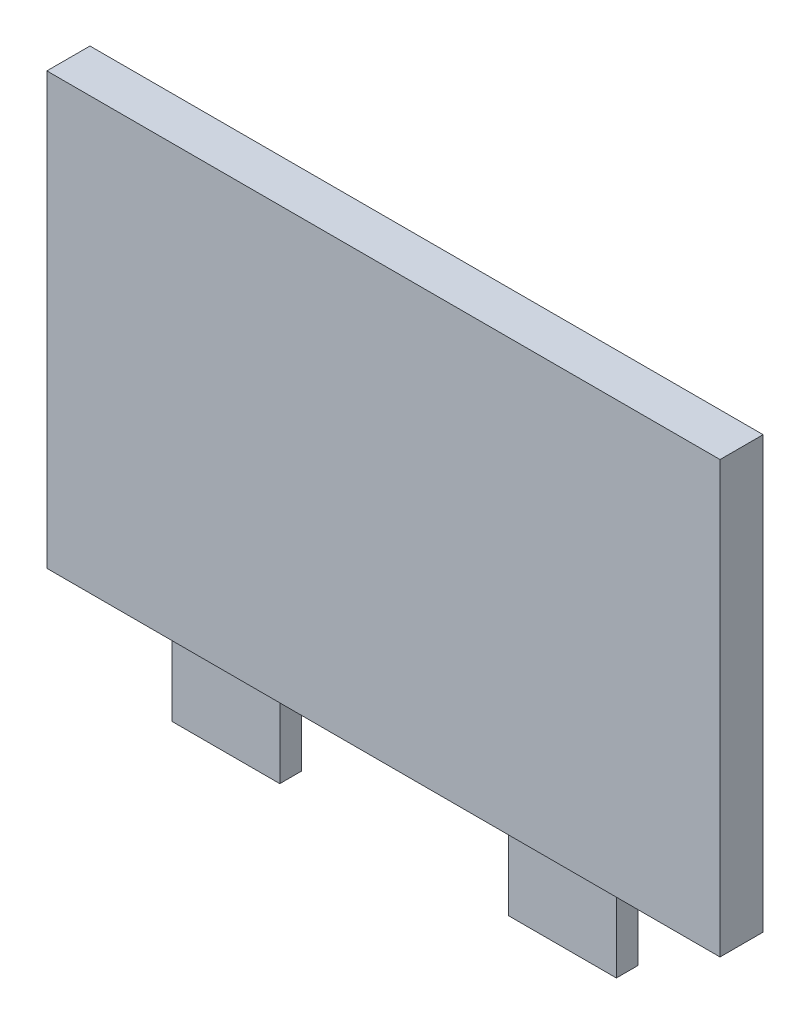
SolidWorks part; units mm, degrees
ref_plane "前视基准面" through (0, 0, 0) normal (0, 0, 1) x (1, 0, 0)
ref_plane "上视基准面" through (0, 0, 0) normal (0, 1, 0) x (1, 0, 0)
ref_plane "右视基准面" through (0, 0, 0) normal (1, 0, 0) x (0, 0, -1)
sketch "草图1" plane through (0, 0, 0) normal (0, 1, 0) x (1, 0, 0)
  line L1 (0, 0) -> (125, 0)
  line L2 (0, 0) -> (0, 8)
  line L3 (0, 8) -> (125, 8)
  line L4 (125, 0) -> (125, 8)
  dimension "D1" = 8
  dimension "D2" = 125
extrude "凸台-拉伸1" add sketch "草图1" along normal blind 80
sketch "草图3" plane through (0, 0, 0) normal (0, -1, 0) x (1, 0, 0)
  line L0 (62.5, -8) -> (62.5, 0) construction
  line L1 (125, -8) -> (0, -8) construction
  line L2 (0, 0) -> (125, 0) construction
  line L3 (0, 0) -> (62.5, -8) construction
  line L4 (62.5, -8) -> (125, 0) construction
  line L5 (0, -8) -> (62.5, 0) construction
  line L6 (62.5, 0) -> (125, -8) construction
  line L8 (21.25, -2) -> (41.25, -2)
  line L9 (21.25, -2) -> (21.25, -6)
  line L10 (21.25, -6) -> (41.25, -6)
  line L11 (41.25, -2) -> (41.25, -6)
  line L12 (21.25, -2) -> (41.25, -6) construction
  line L13 (21.25, -6) -> (41.25, -2) construction
  line L14 (83.75, -2) -> (103.75, -2)
  line L15 (83.75, -2) -> (83.75, -6)
  line L16 (83.75, -6) -> (103.75, -6)
  line L17 (103.75, -2) -> (103.75, -6)
  line L18 (83.75, -2) -> (103.75, -6) construction
  line L19 (83.75, -6) -> (103.75, -2) construction
  point P11 (31.25, -4)
  point P19 (93.75, -4)
extrude "凸台-拉伸2" add sketch "草图3" along normal blind 15
sketch "草图4" plane through (0, 0, -8) normal (0, 0, -1) x (-1, 0, 0)
  line L0 (-125, 35) -> (49875, 35) construction
  line L3 (-125, 0) -> (0, 0) construction
  dimension "D1" = 35
